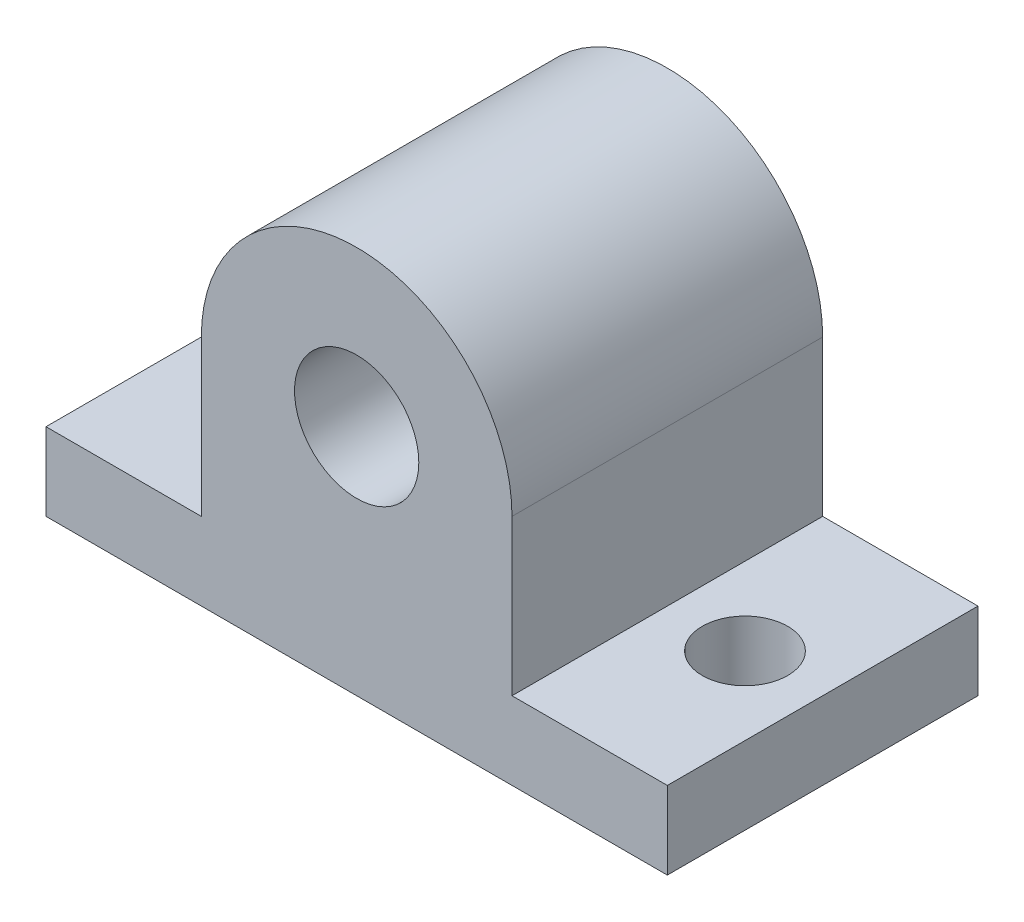
SolidWorks part; units mm, degrees
ref_plane "前视基准面" through (0, 0, 0) normal (0, 0, 1) x (1, 0, 0)
ref_plane "上视基准面" through (0, 0, 0) normal (0, 1, 0) x (1, 0, 0)
ref_plane "右视基准面" through (0, 0, 0) normal (1, 0, 0) x (0, 0, -1)
sketch "草图1" plane through (0, 0, 0) normal (0, 1, 0) x (1, 0, 0)
  line L1 (-16.478, 4.8428) -> (23.522, 4.8428)
  line L2 (-16.478, 4.8428) -> (-16.478, -15.1572)
  line L3 (-16.478, -15.1572) -> (23.522, -15.1572)
  line L4 (23.522, 4.8428) -> (23.522, -15.1572)
  line L5 (-16.478, 4.8428) -> (23.522, -15.1572) construction
  line L6 (-16.478, -15.1572) -> (23.522, 4.8428) construction
  point P4 (3.522, -5.1572)
  dimension "D1" = 40
  dimension "D2" = 20
extrude "凸台-拉伸1" add sketch "草图1" along normal blind 5
sketch "草图2" plane through (0, 0, 15.1572) normal (0, 0, 1) x (1, 0, 0)
  line L0 (3.522, 5) -> (3.522, 8.7926) construction
  line L2 (-16.478, 5) -> (23.522, 5) construction
  line L3 (-6.478, 15) -> (-6.478, 5)
  line L4 (13.522, 15) -> (13.522, 5)
  line L5 (13.522, 5) -> (-6.478, 5)
  circle A0 centre (3.522, 15) radius 4
  arc A1 (13.522, 15) -> (-6.478, 15) centre (3.522, 15) ccw
  dimension "D1" = 8
  dimension "D4" = 6
  dimension "D2" = 3.7926
  dimension "D3" = 10
extrude "凸台-拉伸2" add sketch "草图2" against normal up to surface (20 mm away) up to face at (3.522, 2.5, -4.8428)
sketch "草图3" plane through (0, 5, 0) normal (0, 1, 0) x (1, 0, 0)
  line L0 (-16.478, -5.1572) -> (23.522, -5.1572) construction
  line L1 (-16.478, 4.8428) -> (-16.478, -15.1572) construction
  line L2 (23.522, -15.1572) -> (23.522, 4.8428) construction
  line L3 (-11.478, 4.8428) -> (-11.478, -15.1572) construction
  line L4 (-6.478, 4.8428) -> (-16.478, 4.8428) construction
  line L5 (-16.478, -15.1572) -> (-6.478, -15.1572) construction
  line L6 (18.522, 4.8428) -> (18.522, -15.1572) construction
  line L7 (23.522, 4.8428) -> (13.522, 4.8428) construction
  line L8 (13.522, -15.1572) -> (23.522, -15.1572) construction
  circle A0 centre (-11.478, -5.1572) radius 2.75
  circle A1 centre (18.522, -5.1572) radius 2.75
  dimension "D1" = 5.5
extrude "切除-拉伸1" cut sketch "草图3" against normal through all
